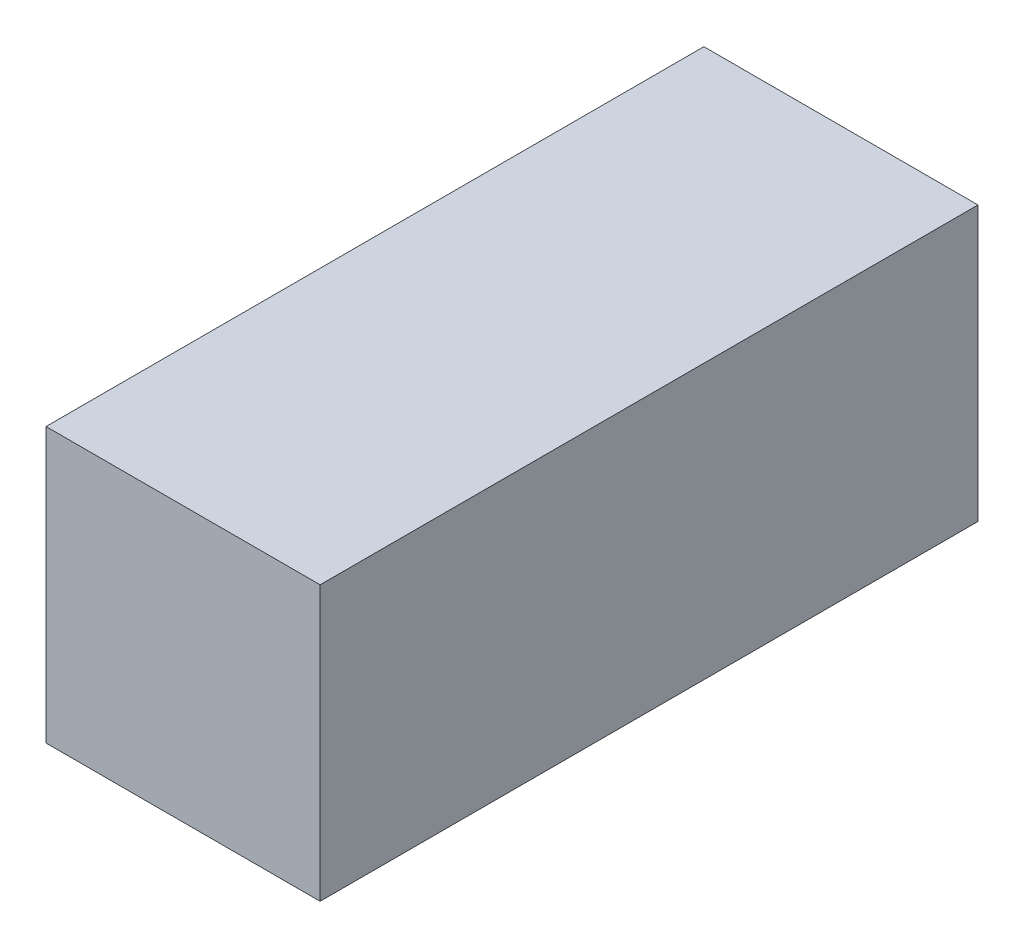
SolidWorks part; units mm, degrees
ref_plane "Front Plane" through (0, 0, 0) normal (0, 0, 1) x (1, 0, 0)
ref_plane "Top Plane" through (0, 0, 0) normal (0, 1, 0) x (1, 0, 0)
ref_plane "Right Plane" through (0, 0, 0) normal (1, 0, 0) x (0, 0, -1)
sketch "Sketch1" plane through (0, 0, 0) normal (0, 0, 1) x (1, 0, 0)
  line L1 (127, -127) -> (-127, -127)
  line L2 (127, -127) -> (127, 127)
  line L3 (127, 127) -> (-127, 127)
  line L4 (-127, -127) -> (-127, 127)
  line L5 (127, -127) -> (-127, 127) construction
  line L6 (127, 127) -> (-127, -127) construction
  point P0 (0, 0)
  dimension "D1" = 254
  dimension "D2" = 254
extrude "Boss-Extrude1" add sketch "Sketch1" along normal blind 609.6
